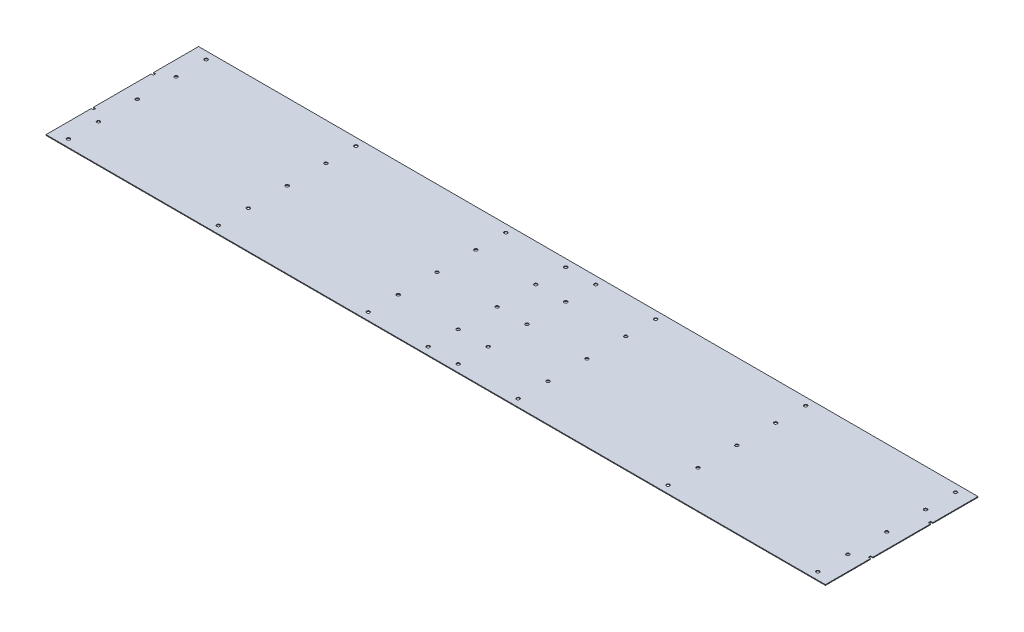
SolidWorks part; units mm, degrees
ref_plane "Front Plane" through (0, 0, 0) normal (0, 0, 1) x (1, 0, 0)
ref_plane "Top Plane" through (0, 0, 0) normal (0, 1, 0) x (1, 0, 0)
ref_plane "Right Plane" through (0, 0, 0) normal (1, 0, 0) x (0, 0, -1)
sketch "Sketch1" plane through (0, 0, 0) normal (0, 1, 0) x (1, 0, 0)
  line L0 (-20, -41.5) -> (-20, -101.8)
  line L1 (-20, -101.8) -> (1020, -101.8)
  line L2 (1020, -101.8) -> (1020, -41.5)
  line L3 (1020, -41.5) -> (-20, -41.5) construction
  line L4 (0, 0) -> (-17, 0) construction
  line L5 (-20, -41.5) -> (-17, -41.5)
  line L7 (-17, 41.5) -> (-20, 41.5)
  line L8 (-20, 41.5) -> (-20, 101.8)
  line L9 (-20, 101.8) -> (1020, 101.8)
  line L10 (1020, 101.8) -> (1020, 41.5)
  line L11 (1020, 41.5) -> (1017, 41.5)
  line L13 (1017, -41.5) -> (1020, -41.5)
  line L14 (0, 51.8) -> (480, 51.8) construction
  line L15 (-17, 41.5) -> (-17, 38.5)
  line L16 (-17, 41.5) -> (1017, 41.5) construction
  line L17 (1017, 41.5) -> (1017, -41.5) construction
  line L18 (-17, 41.5) -> (-17, -41.5) construction
  line L19 (-17, 38.5) -> (-20, 38.5)
  line L20 (-20, 38.5) -> (-20, -38.5)
  line L21 (-20, -38.5) -> (-17, -38.5)
  line L22 (-17, -38.5) -> (-17, -41.5)
  line L23 (1017, 41.5) -> (1017, 38.5)
  line L24 (1017, 38.5) -> (1020, 38.5)
  line L25 (1020, 38.5) -> (1020, -38.5)
  line L26 (1020, -38.5) -> (1017, -38.5)
  line L27 (1017, -38.5) -> (1017, -41.5)
  line L28 (1020, 0) -> (1017, 0) construction
  line L29 (480, 51.8) -> (480, -51.8) construction
  line L30 (-17, 0) -> (-20, 0) construction
  line L31 (0, 51.8) -> (0, -51.8) construction
  line L32 (480, -51.8) -> (0, -51.8) construction
  line L33 (0, 51.8) -> (0, 91.8) construction
  line L34 (0, 91.8) -> (480, 91.8) construction
  line L35 (480, 91.8) -> (480, 51.8) construction
  line L36 (480, -51.8) -> (480, -91.8) construction
  line L37 (480, -91.8) -> (0, -91.8) construction
  line L38 (0, -91.8) -> (0, -51.8) construction
  line L39 (0, 0) -> (480, 0) construction
  line L40 (200, 91.8) -> (200, 51.8) construction
  line L41 (200, 51.8) -> (200, 0) construction
  line L42 (200, 0) -> (200, -51.8) construction
  line L43 (200, -51.8) -> (200, -91.8) construction
  line L44 (500, 101.8) -> (500, -101.8) construction
  line L45 (480, 91.8) -> (500, 91.8) construction
  line L46 (500, 91.8) -> (520, 91.8) construction
  line L47 (520, 91.8) -> (520, -91.8) construction
  line L48 (520, -91.8) -> (480, -91.8) construction
  line L49 (480, -51.8) -> (520, -51.8) construction
  line L50 (400, 91.8) -> (400, -91.8) construction
  line L51 (480, 0) -> (520, 0) construction
  line L53 (480, 51.8) -> (520, 51.8) construction
  line L54 (600, 91.8) -> (600, -91.8) construction
  line L56 (800, 91.8) -> (800, -91.8) construction
  line L58 (1000, 91.8) -> (1000, -91.8) construction
  circle A0 centre (0, -51.8) radius 2.15
  circle A30 centre (0, 51.8) radius 2.15
  circle A31 centre (0, -91.8) radius 2.15
  circle A32 centre (0, 91.8) radius 2.15
  circle A33 centre (200, -91.8) radius 2.15
  circle A34 centre (200, -51.8) radius 2.15
  circle A35 centre (200, 51.8) radius 2.15
  circle A36 centre (200, 91.8) radius 2.15
  circle A53 centre (0, 0) radius 2.15
  circle A54 centre (480, 0) radius 2.15
  circle A55 centre (200, 0) radius 2.15
  circle A59 centre (480, 91.8) radius 2.15
  circle A60 centre (480, 51.8) radius 2.15
  circle A61 centre (480, -51.8) radius 2.15
  circle A62 centre (480, -91.8) radius 2.15
  circle A63 centre (400, -91.8) radius 2.15
  circle A64 centre (400, -51.8) radius 2.15
  circle A65 centre (400, 51.8) radius 2.15
  circle A66 centre (400, 91.8) radius 2.15
  circle A67 centre (600, -91.8) radius 2.15
  circle A68 centre (600, -51.8) radius 2.15
  circle A69 centre (600, 51.8) radius 2.15
  circle A70 centre (600, 91.8) radius 2.15
  circle A71 centre (800, -91.8) radius 2.15
  circle A72 centre (800, -51.8) radius 2.15
  circle A73 centre (800, 51.8) radius 2.15
  circle A74 centre (800, 91.8) radius 2.15
  circle A75 centre (1000, -91.8) radius 2.15
  circle A76 centre (1000, -51.8) radius 2.15
  circle A77 centre (1000, 51.8) radius 2.15
  circle A78 centre (1000, 91.8) radius 2.15
  circle A79 centre (520, -91.8) radius 2.15
  circle A80 centre (520, -51.8) radius 2.15
  circle A81 centre (520, 0) radius 2.15
  circle A82 centre (520, 51.8) radius 2.15
  circle A83 centre (520, 91.8) radius 2.15
  circle A84 centre (600, 0) radius 2.15
  circle A85 centre (800, 0) radius 2.15
  circle A86 centre (1000, 0) radius 2.15
  circle A87 centre (400, 0) radius 2.15
  point P2 (-18.5, 38.5)
  point P17 (0, 71.8)
  dimension "D12" = 4.3
  dimension "D8" = 3
  dimension "D1" = 3
  dimension "D6" = 40
  dimension "D7" = 10
  dimension "D4" = 20
  dimension "D15" = 200
  dimension "D3" = 13.3
  dimension "D11" = 13.3
  dimension "D2" = 77
  dimension "D5" = 20
  dimension "D10" = 40
  dimension "D9" = 6
  dimension "D14" = 2
extrude "Boss-Extrude1" add sketch "Sketch1" along normal blind 1 contours L27 L26 L25 L24 L23 L11 L10 L9 L8 L7 L15 L19 L20 L21 L22 L5 L0 L1 L2 L13 A54 A53 A36 A35 A34 A33 A32 A31 A30 A0
equation "\"skin_sheetmetal_thickness\"= 0.80"
equation "\"base_width_skin_spacer\" = \"base_width_skin_target_width\" - 4 * \"skin_sheetmetal_thickness\" - 2 * \"base_width_skin_target_bend_radius\""
equation "\"base_width_skin_inner\" = \"base_width_skin_spacer\" + 2 * \"skin_sheetmetal_thickness\""
equation "\"base_width_skin_outer\" = \"base_width_skin_inner\" + 2 * \"skin_sheetmetal_thickness\""
equation "\"bend_cut_width\"= 3"
equation "\"bend_cut_length\"= 3"
equation "\"bend_offset_inner\"= 12.5"
equation "\"bend_offset_outer\" = \"bend_offset_inner\" + \"skin_sheetmetal_thickness\""
equation "\"border_offset_ends\"= 20"
equation "\"border_offset_sides\"= 10"
equation "\"border_offset_flange_horiz\"= 10"
equation "\"rivet_size\"= 4.3"
equation "\"rivet_offset_ends\"= \"rivet_spacing_horiz\"/2 - \"border_offset_ends\""
equation "\"rivet_spacing_horiz\"= 200"
equation "\"rivet_spacing_vert\"= 40"
equation "\"rivet_spacing_offset_right\"= 40"
equation "\"base_length\"= 200"
equation "\"base_width_skin_spacer_length\" = 430"
equation "\"bend_offset_spacer_tab\"= 21.0"
equation "\"D6@Sketch1\"=\"rivet_spacing_vert\""
equation "\"D3@Sketch1\"=\"bend_offset_outer\""
equation "\"D1@Sketch1\"=\"bend_cut_length\""
equation "\"D8@Sketch1\"=\"bend_cut_width\""
equation "\"D2@Sketch1\"=\"base_width_skin_outer\""
equation "\"D4@Sketch1\"=\"border_offset_ends\""
equation "\"D7@Sketch1\"=\"border_offset_flange_horiz\""
equation "\"D12@Sketch1\"=\"rivet_size\""
equation "\"D15@Sketch1\"=\"rivet_spacing_horiz\""
equation "\"D5@Sketch1\"=\"border_offset_ends\""
equation "\"D10@Sketch1\"=\"rivet_spacing_offset_right\""
equation "\"base_width_skin_target_width\" = 80"
equation "\"base_width_skin_target_bend_radius\" = 1.5"
